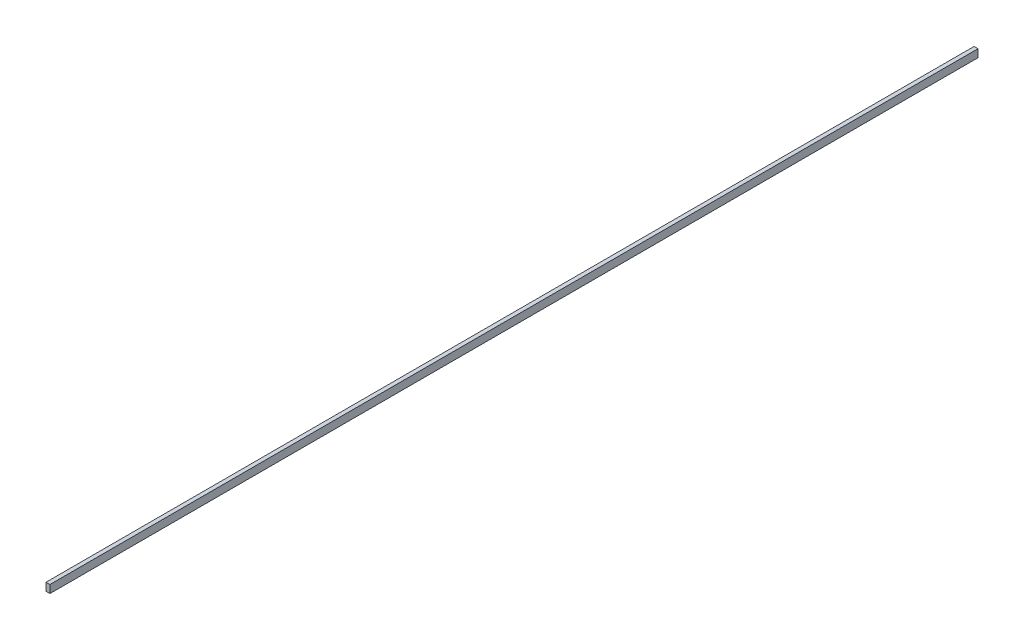
SolidWorks part; units mm, degrees
ref_plane "Alzado" through (0, 0, 0) normal (0, 0, 1) x (1, 0, 0)
ref_plane "Planta" through (0, 0, 0) normal (0, 1, 0) x (1, 0, 0)
ref_plane "Vista lateral" through (0, 0, 0) normal (1, 0, 0) x (0, 0, -1)
sketch "Croquis1" plane through (0, 0, 0) normal (0, 0, 1) x (1, 0, 0)
  line L1 (0, 0) -> (25.4, 0)
  line L2 (0, 0) -> (0, -50.8)
  line L3 (0, -50.8) -> (25.4, -50.8)
  line L4 (25.4, 0) -> (25.4, -50.8)
  dimension "D1" = 25.4
  dimension "D2" = 50.8
extrude "Saliente-Extruir1" add sketch "Croquis1" along normal blind 6000
